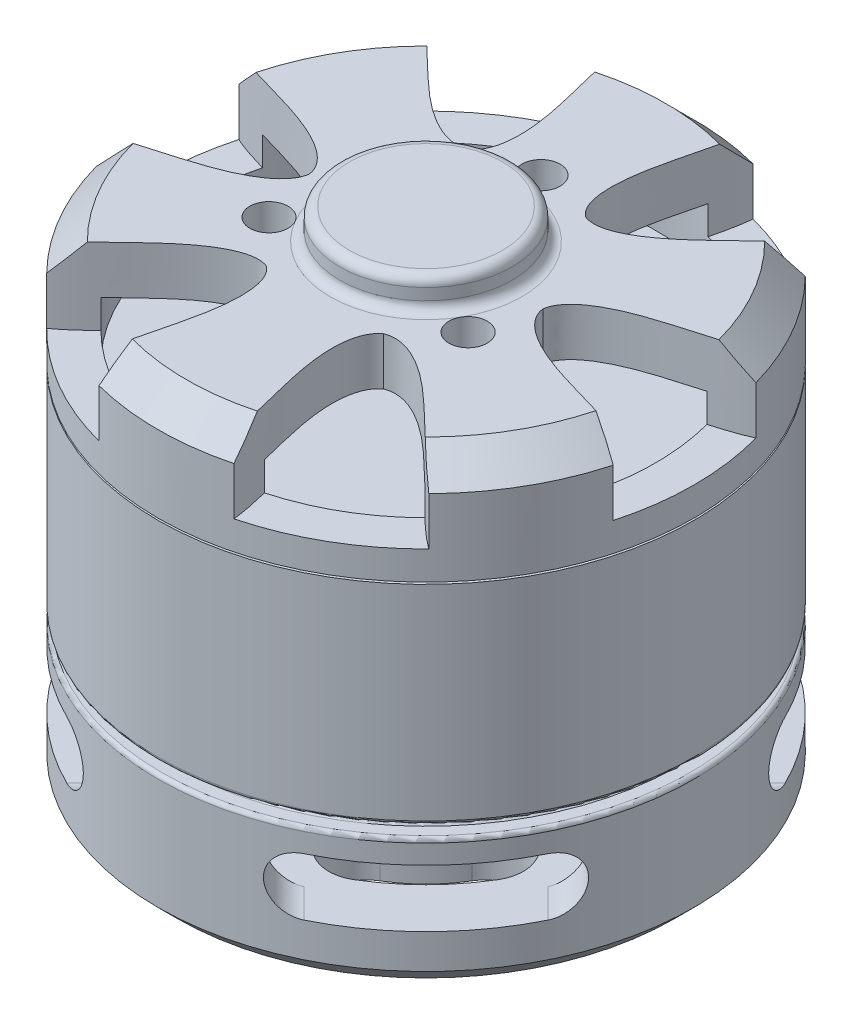
SolidWorks part; units mm, degrees
ref_plane "前视基准面" through (0, 0, 0) normal (0, 0, 1) x (1, 0, 0)
ref_plane "上视基准面" through (0, 0, 0) normal (0, 1, 0) x (1, 0, 0)
ref_plane "右视基准面" through (0, 0, 0) normal (1, 0, 0) x (0, 0, -1)
other "Configuration Table"
sketch "草图1" plane through (0, 0, 0) normal (0, 1, 0) x (1, 0, 0)
  line L0 (-12.8323, 0) -> (11.4175, 0) construction
  line L1 (0, 17.8689) -> (0, -21.1416) construction
  line L2 (0, 0) -> (-6.364, 6.364) construction
  circle A0 centre (0, 0) radius 14
  circle A1 centre (0, 8) radius 1.25
  circle A2 centre (9.5, 0) radius 1.25
  circle A3 centre (0, -8) radius 1.25
  circle A4 centre (-9.5, 0) radius 1.25
  arc A5 (-7.7145, 4.6353) -> (-4.6353, 7.7145) centre (0, 0) cw construction
  arc A6 (-5.6654, 9.4288) -> (-9.4288, 5.6654) centre (0, 0) ccw
  arc A7 (-3.6053, 6.0002) -> (-6.0002, 3.6053) centre (0, 0) ccw
  arc A8 (-3.6053, 6.0002) -> (-5.6654, 9.4288) centre (-4.6353, 7.7145) ccw
  arc A9 (-9.4288, 5.6654) -> (-6.0002, 3.6053) centre (-7.7145, 4.6353) ccw
  arc A10 (6.0002, 3.6053) -> (3.6053, 6.0002) centre (0, 0) ccw
  arc A11 (6.0002, 3.6053) -> (9.4288, 5.6654) centre (7.7145, 4.6353) ccw
  arc A12 (5.6654, 9.4288) -> (3.6053, 6.0002) centre (4.6353, 7.7145) ccw
  arc A13 (9.4288, 5.6654) -> (5.6654, 9.4288) centre (0, 0) ccw
  arc A14 (4.6353, 7.7145) -> (7.7145, 4.6353) centre (0, 0) cw construction
  arc A15 (3.6053, -6.0002) -> (6.0002, -3.6053) centre (0, 0) ccw
  arc A16 (3.6053, -6.0002) -> (5.6654, -9.4288) centre (4.6353, -7.7145) ccw
  arc A17 (9.4288, -5.6654) -> (6.0002, -3.6053) centre (7.7145, -4.6353) ccw
  arc A18 (5.6654, -9.4288) -> (9.4288, -5.6654) centre (0, 0) ccw
  arc A19 (7.7145, -4.6353) -> (4.6353, -7.7145) centre (0, 0) cw construction
  arc A20 (-6.0002, -3.6053) -> (-3.6053, -6.0002) centre (0, 0) ccw
  arc A21 (-6.0002, -3.6053) -> (-9.4288, -5.6654) centre (-7.7145, -4.6353) ccw
  arc A22 (-5.6654, -9.4288) -> (-3.6053, -6.0002) centre (-4.6353, -7.7145) ccw
  arc A23 (-9.4288, -5.6654) -> (-5.6654, -9.4288) centre (0, 0) ccw
  arc A24 (-4.6353, -7.7145) -> (-7.7145, -4.6353) centre (0, 0) cw construction
  point P17 (-6.364, 6.364)
  point P29 (6.364, 6.364)
  point P36 (6.364, -6.364)
  point P43 (-6.364, -6.364)
  point P48 (0, 0)
  dimension "D1" = 28
  dimension "D2" = 2.5
  dimension "D3" = 2.5
  dimension "D4" = 19
  dimension "D5" = 16
  dimension "D7" = 2
  dimension "D9" = 9
  dimension "D6" = 45
  dimension "D8" = 28
  dimension "D10" = 4
extrude "凸台-拉伸1" add sketch "草图1" along normal blind 7
chamfer "倒角2" distance 1 angle 45 1 edges at (0, 0, 14)
sketch "草图2" plane through (0, 7, 0) normal (0, 1, 0) x (1, 0, 0)
  circle A0 centre (0, 0) radius 13
  dimension "D1" = 26
extrude "凸台-拉伸2" add sketch "草图2" along normal blind 0.6
sketch "草图3" plane through (0, 7.6, 0) normal (0, 1, 0) x (1, 0, 0)
  circle A0 centre (0, 0) radius 14
extrude "凸台-拉伸3" add sketch "草图3" along normal blind 10.9
sketch "草图5" plane through (0, 18.5, 0) normal (0, 1, 0) x (1, 0, 0)
  circle A0 centre (0, 0) radius 13.5
  dimension "D1" = 27
extrude "凸台-拉伸4" add sketch "草图5" along normal blind 0.1
sketch "草图6" plane through (0, 18.6, 0) normal (0, 1, 0) x (1, 0, 0)
  circle A0 centre (0, 0) radius 14
  circle A1 centre (0, 0) radius 12
  dimension "D1" = 28
  dimension "D2" = 2
extrude "凸台-拉伸5" add sketch "草图6" along normal blind 3
sketch "草图8" plane through (0, 21.6, 0) normal (0, 1, 0) x (1, 0, 0)
  circle A0 centre (0, 0) radius 14
  dimension "D1" = 28
extrude "凸台-拉伸6" add sketch "草图8" along normal blind 2.5
chamfer "倒角1" distance 1.5 angle 45 1 edges at (0, 24.1, 14)
sketch "草图10" plane through (0, 24.1, 0) normal (0, 1, 0) x (1, 0, 0)
  line L0 (0, 14.745) -> (0, 0) construction
  line L1 (0, 0) -> (7.5472, 13.0721) construction
  line L2 (2.4873, 16.0942) -> (2.4873, 18.7746)
  line L3 (2.4873, 18.7746) -> (10.1474, 18.0073)
  line L4 (10.1474, 18.0073) -> (15.4804, 10.8347)
  line L5 (15.4804, 10.8347) -> (12.6943, 10.2011)
  line L7 (15.1816, 5.8931) -> (17.5029, 7.2333)
  line L8 (17.5029, 7.2333) -> (20.6685, 0.2158)
  line L9 (20.6685, 0.2158) -> (17.1233, -7.9891)
  line L10 (17.1233, -7.9891) -> (15.1816, -5.8931)
  line L11 (12.6943, -10.2011) -> (15.0156, -11.5413)
  line L12 (15.0156, -11.5413) -> (10.5211, -17.7915)
  line L13 (10.5211, -17.7915) -> (1.6429, -18.8237)
  line L14 (1.6429, -18.8237) -> (2.4873, -16.0942)
  line L15 (-2.4873, -16.0942) -> (-2.4873, -18.7746)
  line L16 (-2.4873, -18.7746) -> (-10.1474, -18.0073)
  line L17 (-10.1474, -18.0073) -> (-15.4804, -10.8347)
  line L18 (-15.4804, -10.8347) -> (-12.6943, -10.2011)
  line L19 (-15.1816, -5.8931) -> (-17.5029, -7.2333)
  line L20 (-17.5029, -7.2333) -> (-20.6685, -0.2158)
  line L21 (-20.6685, -0.2158) -> (-17.1233, 7.9891)
  line L22 (-17.1233, 7.9891) -> (-15.1816, 5.8931)
  line L23 (-12.6943, 10.2011) -> (-15.0156, 11.5413)
  line L24 (-15.0156, 11.5413) -> (-10.5211, 17.7915)
  line L25 (-10.5211, 17.7915) -> (-1.6429, 18.8237)
  line L26 (-1.6429, 18.8237) -> (-2.4873, 16.0942)
  spline S0 degree 3 poles (2.4873, 16.0942) (4.6567, 15.0736) (2.1032, 9.9112) (2.3365, 5.8216) (3.0482, 5.2796) knots 0 0 0 0 0.562936 0.825224 0.825224 0.825224 0.825224
  spline S1 degree 3 poles (12.6943, 10.2011) (10.7258, 11.5696) (7.5317, 6.7771) (3.8734, 4.9343) (3.0482, 5.2796) knots 0 0 0 0 0.562936 0.825224 0.825224 0.825224 0.825224
  spline S2 degree 3 poles (15.1816, -5.8931) (15.3825, -3.504) (9.635, -3.1341) (6.2099, -0.8873) (6.0963, 0) knots 0 0 0 0 0.562936 0.825224 0.825224 0.825224 0.825224
  spline S3 degree 3 poles (15.1816, 5.8931) (15.3825, 3.504) (9.635, 3.1341) (6.2099, 0.8873) (6.0963, 0) knots 0 0 0 0 0.562936 0.825224 0.825224 0.825224 0.825224
  spline S4 degree 3 poles (2.4873, -16.0942) (4.6567, -15.0736) (2.1032, -9.9112) (2.3365, -5.8216) (3.0482, -5.2796) knots 0 0 0 0 0.562936 0.825224 0.825224 0.825224 0.825224
  spline S5 degree 3 poles (12.6943, -10.2011) (10.7258, -11.5696) (7.5317, -6.7771) (3.8734, -4.9343) (3.0482, -5.2796) knots 0 0 0 0 0.562936 0.825224 0.825224 0.825224 0.825224
  spline S6 degree 3 poles (-12.6943, -10.2011) (-10.7258, -11.5696) (-7.5317, -6.7771) (-3.8734, -4.9343) (-3.0482, -5.2796) knots 0 0 0 0 0.562936 0.825224 0.825224 0.825224 0.825224
  spline S7 degree 3 poles (-2.4873, -16.0942) (-4.6567, -15.0736) (-2.1032, -9.9112) (-2.3365, -5.8216) (-3.0482, -5.2796) knots 0 0 0 0 0.562936 0.825224 0.825224 0.825224 0.825224
  spline S8 degree 3 poles (-15.1816, 5.8931) (-15.3825, 3.504) (-9.635, 3.1341) (-6.2099, 0.8873) (-6.0963, 0) knots 0 0 0 0 0.562936 0.825224 0.825224 0.825224 0.825224
  spline S9 degree 3 poles (-15.1816, -5.8931) (-15.3825, -3.504) (-9.635, -3.1341) (-6.2099, -0.8873) (-6.0963, 0) knots 0 0 0 0 0.562936 0.825224 0.825224 0.825224 0.825224
  spline S10 degree 3 poles (-2.4873, 16.0942) (-4.6567, 15.0736) (-2.1032, 9.9112) (-2.3365, 5.8216) (-3.0482, 5.2796) knots 0 0 0 0 0.562936 0.825224 0.825224 0.825224 0.825224
  spline S11 degree 3 poles (-12.6943, 10.2011) (-10.7258, 11.5696) (-7.5317, 6.7771) (-3.8734, 4.9343) (-3.0482, 5.2796) knots 0 0 0 0 0.562936 0.825224 0.825224 0.825224 0.825224
  point P52 (0, 0)
  point P66 (0, 0)
  dimension "D1" = 30
extrude "切除-拉伸2" cut sketch "草图10" against normal blind 4
sketch "草图11" plane through (0, 24.1, 0) normal (0, 1, 0) x (1, 0, 0)
  circle A0 centre (0, 0) radius 4.5
  dimension "D1" = 9
extrude "凸台-拉伸7" add sketch "草图11" along normal blind 1.6
fillet "圆角1" radius 0.5 2 edges at (0, 24.1, 4.5) (0, 25.7, 4.5)
fillet "圆角2" radius 0.2 4 edges at (0, 7.6, 14) (0, 7, 13) (0, 7.6, 13) (0, 7, 14)
sketch "草图12" plane through (0, 0, 0) normal (0, -1, 0) x (-1, 0, 0)
  circle A0 centre (0, 0) radius 3
  dimension "D1" = 6
extrude "凸台-拉伸8" add sketch "草图12" along normal blind 1.6
fillet "圆角3" radius 1 1 edges at (0, -1.6, -3)
sketch "草图13" plane through (0, 24.1, 0) normal (0, 1, 0) x (1, 0, 0)
  circle A0 centre (0, 6) radius 1
  circle A1 centre (5.1962, -3) radius 1
  circle A2 centre (-5.1962, -3) radius 1
  point P10 (0, 0)
  dimension "D1" = 6
  dimension "D2" = 2
extrude "切除-拉伸3" cut sketch "草图13" against normal up to next
ref_plane "基准面1" through (0, 0, 0) normal (-0.7071, 0, 0.7071) x (0.7071, 0, 0.7071)
sketch "草图14" plane through (0, 0, 0) normal (-0.7071, 0, 0.7071) x (0.7071, 0, 0.7071)
  line L0 (0, -3.1894) -> (0, 10.1312) construction
  line L1 (-4.5, 4.3) -> (4.5, 4.3) construction
  line L2 (-4.5, 5.8) -> (4.5, 5.8)
  line L3 (-4.5, 2.8) -> (4.5, 2.8)
  line L4 (-14, 6.8) -> (14, 6.8) construction
  arc A0 (-4.5, 5.8) -> (-4.5, 2.8) centre (-4.5, 4.3) ccw
  arc A1 (4.5, 2.8) -> (4.5, 5.8) centre (4.5, 4.3) ccw
  point P5 (0, 4.3)
  dimension "D2" = 1.5
  dimension "D1" = 1
  dimension "D3" = 9
extrude "切除-拉伸4" cut sketch "草图14" against normal mid plane 50
pattern_circular "阵列(圆周)1" count 2 every 90 about axis through (0, 0, 0) along (0, 1, 0) of "切除-拉伸4"
sketch "草图15" plane through (0, 2.8, 0) normal (0, 1, 0) x (1, 0, 0)
  circle A0 centre (0, 0) radius 12
extrude "切除-拉伸5" cut sketch "草图15" along normal up to surface (4.2 mm away) up to face at (-6.0984, 7, -6.0984)
